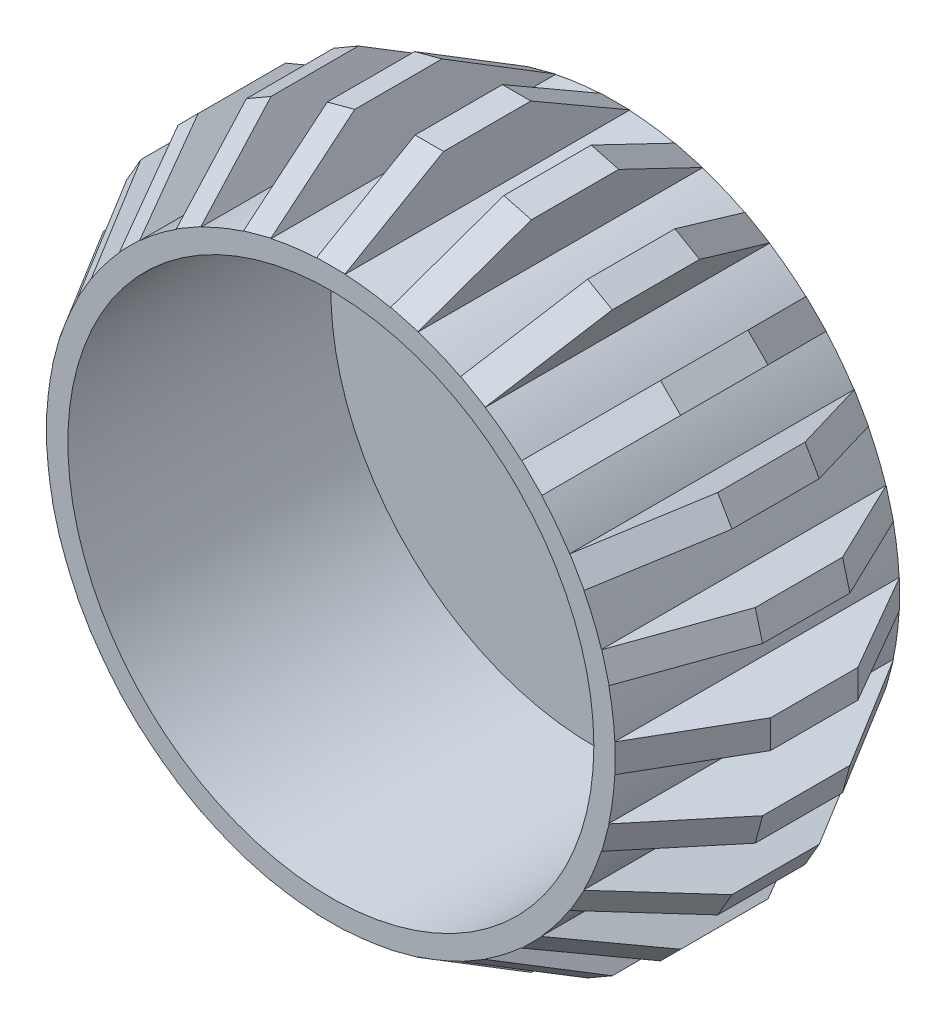
SolidWorks part; units mm, degrees
ref_plane "Front Plane" through (0, 0, 0) normal (0, 0, 1) x (1, 0, 0)
ref_plane "Top Plane" through (0, 0, 0) normal (0, 1, 0) x (1, 0, 0)
ref_plane "Right Plane" through (0, 0, 0) normal (1, 0, 0) x (0, 0, -1)
sketch "Sketch1" plane through (0, 0, 0) normal (0, 0, 1) x (1, 0, 0)
  circle A0 centre (0, 0) radius 20
  circle A1 centre (0, 0) radius 2.5
  dimension "D1" = 5
  dimension "D2" = 40
extrude "Boss-Extrude1" add sketch "Sketch1" along normal blind 1.5
sketch "Sketch2" plane through (0, 0, 1.5) normal (0, 0, 1) x (1, 0, 0)
  circle A0 centre (0, 0) radius 20
  circle A1 centre (0, 0) radius 18.5
  dimension "D1" = 40
  dimension "D2" = 37
extrude "Boss-Extrude2" add sketch "Sketch2" along normal blind 18.5
sketch "Sketch4" plane through (0, 0, 0) normal (0, 0, -1) x (-1, 0, 0)
  line L0 (0, 0) -> (-19, 0) construction
  line L1 (-24, 1) -> (-19, 1)
  line L2 (-24, 1) -> (-24, -1)
  line L3 (-24, -1) -> (-19, -1)
  line L4 (-19, 1) -> (-19, -1)
  dimension "D1" = 2
  dimension "D2" = 19
  dimension "D3" = 5
extrude "Boss-Extrude3" add sketch "Sketch4" against normal blind 20
pattern_circular "CirPattern2" count 24 over 360 about axis through (0, 0, 0) along (0, 0, 1) of "Boss-Extrude3"
chamfer "Chamfer4" distance 4 angle 60 24 edges at (20.7846, -12, 20) (16.9706, -16.9706, 20) (12, -20.7846, 20) (6.2117, -23.1822, 20) (0, -24, 20) (-6.2117, -23.1822, 20) (-12, -20.7846, 20) (-16.9706, -16.9706, 20) (-20.7846, -12, 20) (-23.1822, -6.2117, 20) (-24, 0, 20) (-23.1822, 6.2117, 20) (-20.7846, 12, 20) (-16.9706, 16.9706, 20) (-12, 20.7846, 20) (-6.2117, 23.1822, 20) (0, 24, 20) (6.2117, 23.1822, 20) (12, 20.7846, 20) (16.9706, 16.9706, 20) (20.7846, 12, 20) (23.1822, 6.2117, 20) (24, 0, 20) (23.1822, -6.2117, 20)
chamfer "Chamfer5" distance 4 angle 60 24 edges at (-6.2117, -23.1822, 0) (0, -24, 0) (6.2117, -23.1822, 0) (12, -20.7846, 0) (16.9706, -16.9706, 0) (20.7846, -12, 0) (23.1822, -6.2117, 0) (24, 0, 0) (23.1822, 6.2117, 0) (20.7846, 12, 0) (16.9706, 16.9706, 0) (12, 20.7846, 0) (6.2117, 23.1822, 0) (0, 24, 0) (-6.2117, 23.1822, 0) (-12, 20.7846, 0) (-16.9706, 16.9706, 0) (-20.7846, 12, 0) (-23.1822, 6.2117, 0) (-24, 0, 0) (-23.1822, -6.2117, 0) (-20.7846, -12, 0) (-16.9706, -16.9706, 0) (-12, -20.7846, 0)
